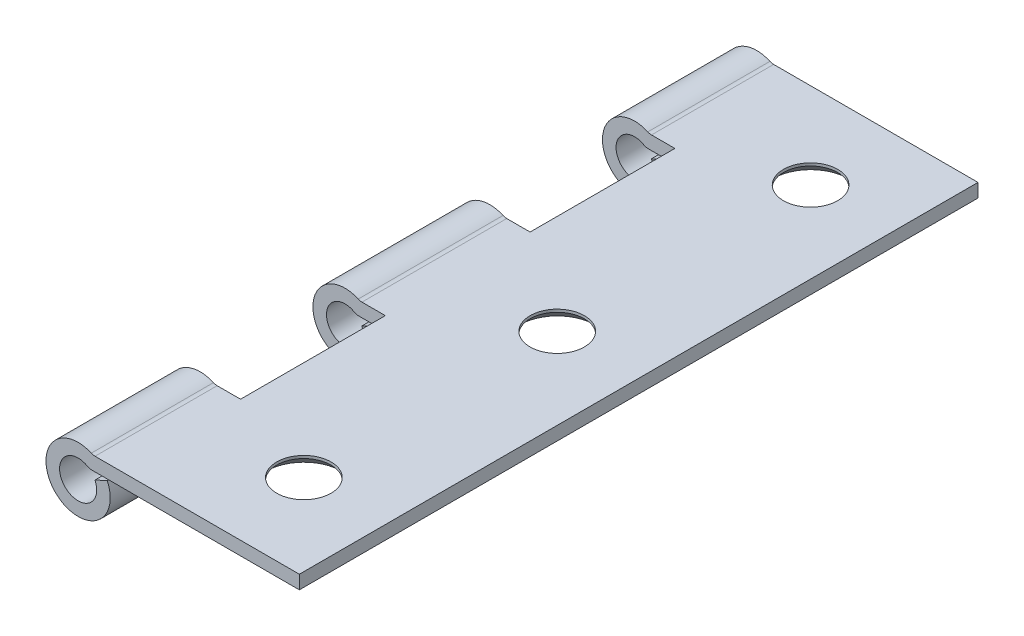
SolidWorks part; units mm, degrees
material "Plain Carbon Steel"
ref_plane "Front Plane" through (0, 0, 0) normal (0, 0, 1) x (1, 0, 0)
ref_plane "Top Plane" through (0, 0, 0) normal (0, 1, 0) x (1, 0, 0)
ref_plane "Right Plane" through (0, 0, 0) normal (1, 0, 0) x (0, 0, -1)
sketch "Sketch1" plane through (0, 0, 0) normal (0, 0, 1) x (1, 0, 0)
  line L0 (1.8655, 3.15) -> (24.45, 3.15)
  line L1 (1.51, 1.65) -> (24.45, 1.65)
  line L2 (3.2174, 1.5003) -> (1.8579, 0.8664)
  line L3 (1.8579, 0.8664) -> (0, 0) construction
  line L4 (0, 0) -> (2.872, 0) construction
  line L5 (24.45, 3.15) -> (24.45, 1.65)
  arc A0 (1.0149, 1.7811) -> (1.8579, 0.8664) centre (0, 0) ccw
  arc A1 (1.4555, 3.2379) -> (3.2174, 1.5003) centre (0, 0) ccw
  arc A2 (1.8655, 3.15) -> (1.4555, 3.2379) centre (1.8655, 4.15) cw
  arc A3 (1.51, 1.65) -> (1.0149, 1.7811) centre (1.51, 2.65) cw
  dimension "D1" = 7.1
  dimension "D2" = 1.5
  dimension "D5" = 1
  dimension "D7" = 28
  dimension "D8" = 2.05
  dimension "D3" = 1.5
  dimension "D4" = 5.2
  dimension "D6" = 25
extrude "Boss-Extrude1" add sketch "Sketch1" along normal mid plane 75
sketch "Sketch2" plane through (0, 1.65, 0) normal (0, -1, 0) x (1, 0, 0)
  line L0 (-3.55, 37.5) -> (-3.55, -37.5) construction
  line L1 (-3.55, -8) -> (4.45, -8)
  line L2 (-3.55, -8) -> (-3.55, -24)
  line L3 (-3.55, -24) -> (4.45, -24)
  line L4 (4.45, -8) -> (4.45, -24)
  line L5 (24.45, 37.5) -> (24.45, -37.5) construction
  dimension "D1" = 20
  dimension "D2" = 16
  dimension "D3" = 8
sketch "Sketch4" plane through (0, 1.65, 0) normal (0, -1, 0) x (1, 0, 0)
  line L0 (24.45, 37.5) -> (24.45, -37.5) construction
  circle A0 centre (15.45, 0) radius 3
  dimension "D1" = 6
  dimension "D2" = 9
extrude "Cut-Extrude3" cut sketch "Sketch4" against normal through all
pattern_linear "LPattern1" count 2 spacing 28 along (0, 0, -1) of "Cut-Extrude3"
mirror "Mirror1" about plane through (0, 0, 0) normal (0, 0, 1) of "LPattern1"
chamfer "Chamfer1" distance 1.2 angle 45 3 edges at (15.45, 1.65, -31) (15.45, 1.65, -3) (15.45, 1.65, 31)
extrude "Cut-Extrude4" cut sketch "Sketch2" against normal through all both and the other way through all
mirror "Mirror2" about plane through (0, 0, 0) normal (0, 0, 1) of "Cut-Extrude4"
